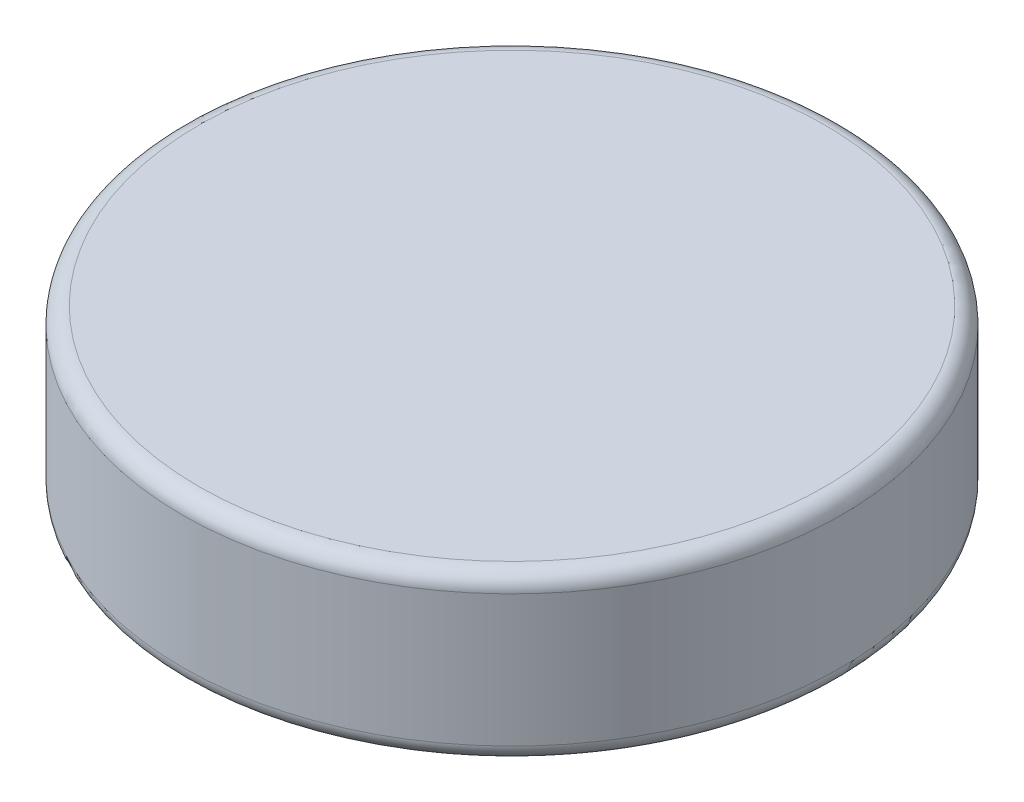
SolidWorks part; units mm, degrees
material "Neodymium Magnet"
ref_plane "Front Plane" through (0, 0, 0) normal (0, 0, 1) x (1, 0, 0)
ref_plane "Top Plane" through (0, 0, 0) normal (0, 1, 0) x (1, 0, 0)
ref_plane "Right Plane" through (0, 0, 0) normal (1, 0, 0) x (0, 0, -1)
sketch "Sketch1" plane through (0, 0, 0) normal (0, 1, 0) x (1, 0, 0)
  circle A0 centre (0, 0) radius 6.35
  dimension "OD" = 12.7
extrude "Boss-Extrude1" add sketch "Sketch1" along normal mid plane 3.175
fillet "Fillet1" radius 0.3175 2 edges at (0, -1.5875, 6.35) (0, 1.5875, 6.35)
equation "\"D1@Fillet1\"=\"Thickness@Boss-Extrude1\"/10"
